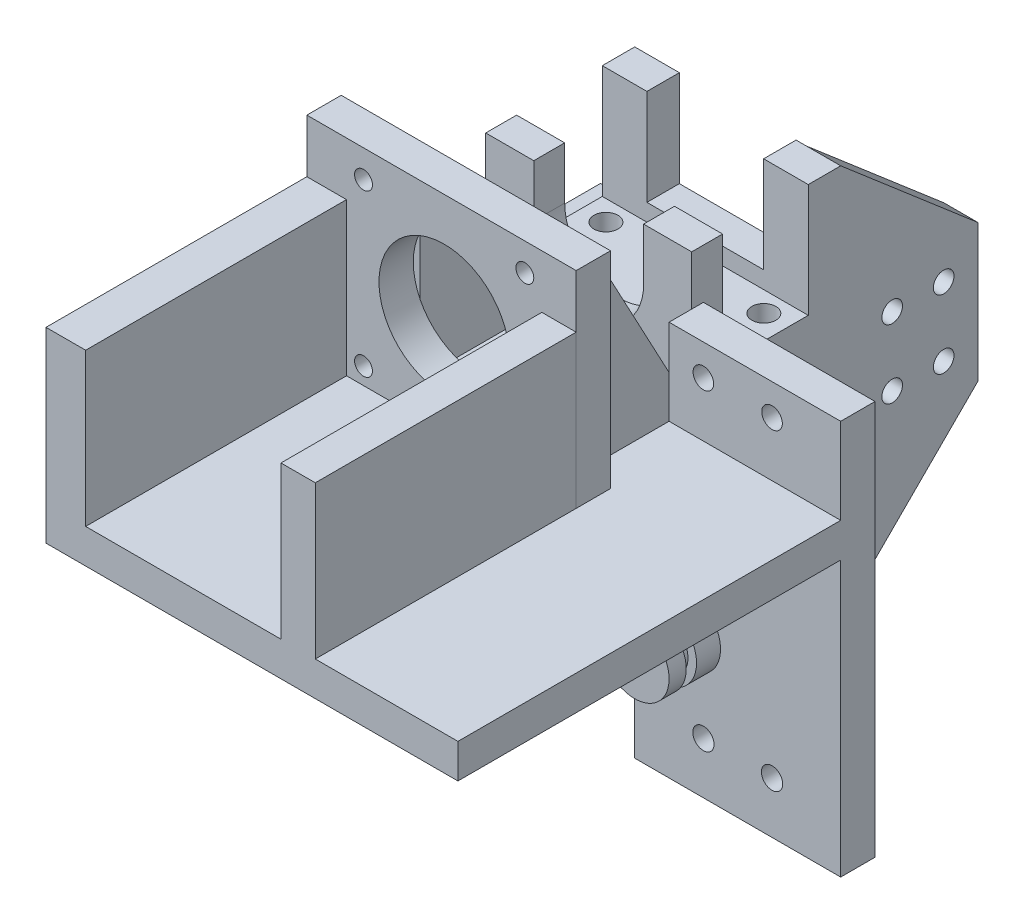
SolidWorks part; units mm, degrees
ref_plane "Front Plane" through (0, 0, 0) normal (0, 0, 1) x (1, 0, 0)
ref_plane "Top Plane" through (0, 0, 0) normal (0, 1, 0) x (1, 0, 0)
ref_plane "Right Plane" through (0, 0, 0) normal (1, 0, 0) x (0, 0, -1)
sketch "Sketch1" plane through (0, 0, 0) normal (0, 1, 0) x (1, 0, 0)
  line L0 (0, 0) -> (0, 161.51)
  line L1 (0, 161.51) -> (60, 161.51)
  line L2 (60, 161.51) -> (60, 121.51)
  line L3 (60, 121.51) -> (110, 121.51)
  line L4 (110, 121.51) -> (110, 0)
  line L5 (110, 0) -> (0, 0)
  dimension "D1" = 161.51
  dimension "D2" = 60
  dimension "D3" = 50
  dimension "D4" = 121.51
extrude "Boss-Extrude1" add sketch "Sketch1" along normal blind 10
sketch "Sketch2" plane through (0, 10, 0) normal (0, 1, 0) x (1, 0, 0)
  line L0 (0, 161.51) -> (0, 0) construction
  line L1 (0, 152.1) -> (60, 152.1)
  line L2 (0, 152.1) -> (0, 127.1)
  line L3 (0, 127.1) -> (60, 127.1)
  line L4 (60, 152.1) -> (60, 127.1)
  line L5 (60, 121.51) -> (60, 161.51) construction
  line L6 (60, 161.51) -> (0, 161.51) construction
  dimension "D1" = 9.41
  dimension "D2" = 25
extrude "Boss-Extrude2" add sketch "Sketch2" along normal blind 6.45
sketch "Sketch3" plane through (0, 10, 0) normal (0, 1, 0) x (1, 0, 0)
  line L0 (60, 152.1) -> (60, 161.51) construction
  line L1 (0, 161.51) -> (60, 161.51)
  line L2 (0, 161.51) -> (0, 152.06)
  line L3 (0, 152.06) -> (60, 152.06)
  line L4 (60, 161.51) -> (60, 152.06)
  dimension "D1" = 9.45
extrude "Boss-Extrude3" add sketch "Sketch3" along normal blind 39.45
sketch "Sketch4" plane through (0, 0, -161.51) normal (0, 0, -1) x (-1, 0, 0)
  line L0 (-60, 49.45) -> (0, 49.45) construction
  line L1 (-47, 49.45) -> (-13, 49.45)
  line L2 (-47, 49.45) -> (-47, 21.45)
  line L3 (-47, 21.45) -> (-13, 21.45)
  line L4 (-13, 49.45) -> (-13, 21.45)
  line L5 (-60, 49.45) -> (-60, 0) construction
  line L6 (0, 49.45) -> (0, 0) construction
  dimension "D1" = 13
  dimension "D2" = 13
  dimension "D3" = 28
extrude "Cut-Extrude1" cut sketch "Sketch4" against normal blind 9.45
sketch "Sketch5" plane through (0, 10, 0) normal (0, 1, 0) x (1, 0, 0)
  line L0 (60, 127.1) -> (60, 152.06) construction
  line L1 (0, 127.1) -> (60, 127.1)
  line L2 (0, 127.1) -> (0, 118.1)
  line L3 (0, 118.1) -> (60, 118.1)
  line L4 (60, 127.1) -> (60, 118.1)
  dimension "D1" = 9
extrude "Boss-Extrude4" add sketch "Sketch5" along normal blind 39.45
sketch "Sketch6" plane through (0, 0, -118.1) normal (0, 0, 1) x (1, 0, 0)
  line L0 (30, 49.45) -> (30, 10) construction
  line L1 (0, 49.45) -> (60, 49.45) construction
  line L2 (0, 10) -> (60, 10) construction
  line L3 (14, 34.24) -> (14, 49.45)
  line L4 (14, 49.45) -> (46, 49.45)
  line L5 (46, 49.45) -> (46, 34.24)
  arc A0 (14, 34.24) -> (46, 34.24) centre (30, 34.24) ccw
  dimension "D1" = 16
  dimension "D2" = 15.21
extrude "Cut-Extrude2" cut sketch "Sketch6" against normal up to next
sketch "Sketch7" plane through (0, 0, 0) normal (0, -1, 0) x (1, 0, 0)
  line L0 (110, -111.51) -> (50, -111.51)
  line L1 (110, 0) -> (110, -121.51) construction
  line L2 (50, -111.51) -> (50, -161.51)
  line L3 (60, -161.51) -> (0, -161.51) construction
  line L4 (50, -161.51) -> (60, -161.51)
  line L5 (60, -161.51) -> (60, -121.51)
  line L6 (60, -121.51) -> (110, -121.51)
  line L7 (110, -121.51) -> (110, -111.51)
  dimension "D1" = 10
  dimension "D2" = 10
extrude "Boss-Extrude5" add sketch "Sketch7" along normal blind 80
sketch "Sketch8" plane through (0, 0, 0) normal (-1, 0, 0) x (0, 0, 1)
  line L0 (-161.51, 0) -> (0, 0) construction
  line L1 (-75.9971, 0) -> (0, 0)
  line L2 (-75.9971, 0) -> (-75.9971, 54.4584)
  line L3 (-75.9971, 54.4584) -> (0, 54.4584)
  line L4 (0, 0) -> (0, 54.4584)
  line L5 (0, 10) -> (0, 0) construction
  dimension "D1" = 75.9971
extrude "Boss-Extrude6" add sketch "Sketch8" along normal blind 10
sketch "Sketch9" plane through (0, 10, 0) normal (0, 1, 0) x (1, 0, 0)
  line L0 (0, 0) -> (110, 0) construction
  line L1 (58.45, 75.9971) -> (68.45, 75.9971)
  line L2 (58.45, 75.9971) -> (58.45, 0)
  line L3 (58.45, 0) -> (68.45, 0)
  line L4 (68.45, 75.9971) -> (68.45, 0)
  line L5 (0, 0) -> (0, 75.9971) construction
  line L6 (-10, 75.9971) -> (0, 75.9971) construction
  dimension "D1" = 58.45
  dimension "D2" = 10
extrude "Boss-Extrude7" add sketch "Sketch9" along normal blind 44.46
sketch "Sketch17" plane through (0, 10, 0) normal (0, 1, 0) x (1, 0, 0)
  line L0 (0, 0) -> (58.45, 0) construction
  line L1 (68.45, 86) -> (-10, 86)
  line L2 (68.45, 86) -> (68.45, 76)
  line L3 (68.45, 76) -> (-10, 76)
  line L4 (-10, 86) -> (-10, 76)
  line L5 (-10, 0) -> (-10, 75.9971) construction
  dimension "D1" = 78.45
  dimension "D2" = 10
  dimension "D3" = 76
  dimension "D4" = 78.45
extrude "Boss-Extrude27" add sketch "Sketch17" along normal blind 60
sketch "Sketch19" plane through (0, 0, -86) normal (0, 0, -1) x (-1, 0, 0)
  line L0 (0, 10) -> (10, 10) construction
  line L1 (0, 70) -> (-2.5, 70)
  line L2 (0, 70) -> (0, 10)
  line L3 (0, 10) -> (-2.5, 10)
  line L4 (-2.5, 70) -> (-2.5, 10)
  line L5 (10, 70) -> (10, 10) construction
  line L6 (-68.45, 70) -> (10, 70) construction
  line L7 (-13, 70) -> (-10.5, 70)
  line L8 (-13, 70) -> (-13, 10)
  line L9 (-13, 10) -> (-10.5, 10)
  line L10 (-10.5, 70) -> (-10.5, 10)
  line L12 (-47, 70) -> (-49.5, 70)
  line L13 (-47, 70) -> (-47, 10)
  line L14 (-47, 10) -> (-49.5, 10)
  line L15 (-49.5, 70) -> (-49.5, 10)
  line L16 (-57.5, 70) -> (-60, 70)
  line L17 (-57.5, 70) -> (-57.5, 10)
  line L18 (-57.5, 10) -> (-60, 10)
  line L19 (-60, 70) -> (-60, 10)
  dimension "D1" = 10
  dimension "D2" = 2.5
  dimension "D3" = 60
  dimension "D4" = 8
  dimension "D5" = 2.5
  dimension "D6" = 60
  dimension "D7" = 2.5
  dimension "D8" = 8
  dimension "D9" = 2.5
  dimension "D10" = 60
  dimension "D11" = 60
  dimension "D12" = 34
extrude "Boss-Extrude31" add sketch "Sketch19" along normal blind 32
sketch "Sketch20" plane through (0, 0, 0) normal (1, 0, 0) x (0, 0, -1)
  line L1 (0, 54.4584) -> (75.9971, 54.4584)
  line L2 (0, 54.4584) -> (0, 10)
  line L3 (0, 10) -> (75.9971, 10)
  line L4 (75.9971, 54.4584) -> (75.9971, 10)
extrude "Boss-Extrude32" add sketch "Sketch20" along normal blind 1.55
sketch "Sketch21" plane through (0, 0, -76) normal (0, 0, 1) x (1, 0, 0)
  line L0 (-10, 70) -> (-10, 10) construction
  line L1 (-10, 70) -> (68.45, 70) construction
  line L2 (53.5, 61.95) -> (6.5, 14.95) construction
  line L3 (53.5, 14.95) -> (6.5, 61.95) construction
  circle A0 centre (6.5, 61.95) radius 2.6
  circle A1 centre (53.5, 61.95) radius 2.6
  circle A2 centre (53.5, 14.95) radius 2.6
  circle A3 centre (6.5, 14.95) radius 2.6
  circle A4 centre (30, 38.45) radius 19
  dimension "D5" = 5.2
  dimension "D6" = 38
  dimension "D1" = 16.5
  dimension "D2" = 8.05
  dimension "D3" = 47
  dimension "D4" = 47
extrude "Cut-Extrude3" cut sketch "Sketch21" against normal blind 10
sketch "Sketch22" plane through (0, 0, 0) normal (0, -1, 0) x (1, 0, 0)
  line L0 (50, -161.51) -> (0, -161.51) construction
  line L1 (0, -161.51) -> (0, -75.9971) construction
  circle A0 centre (7.02, -146.1) radius 3.5
  circle A1 centre (7.02, -133) radius 3.5
  circle A2 centre (53.02, -146.1) radius 3.5
  circle A3 centre (53.02, -133) radius 3.5
  dimension "D4" = 7
  dimension "D1" = 13.1
  dimension "D2" = 15.41
  dimension "D3" = 7.02
  dimension "D5" = 46
extrude "Cut-Extrude4" cut sketch "Sketch22" against normal up to next
sketch "Sketch23" plane through (50, 0, 0) normal (-1, 0, 0) x (0, 0, 1)
  line L0 (-147.8691, 0) -> (-161.51, 0) construction
  line L1 (-153.1, 0) -> (-126.1, 0)
  line L2 (-153.1, 0) -> (-153.1, -6)
  line L3 (-153.1, -6) -> (-126.1, -6)
  line L4 (-126.1, 0) -> (-126.1, -6)
  line L10 (-161.51, -80) -> (-161.51, 0) construction
  dimension "D1" = 27
  dimension "D2" = 8.41
  dimension "D3" = 6
extrude "Cut-Extrude5" cut sketch "Sketch23" against normal up to next
sketch "Sketch24" plane through (50, 0, 0) normal (-1, 0, 0) x (0, 0, 1)
  line L0 (-161.51, -80) -> (-161.51, 0) construction
  line L1 (-111.51, -80) -> (-111.51, 0) construction
  line L2 (-111.51, -80) -> (-161.51, -80) construction
  circle A0 centre (-151.51, -15) radius 3.1
  circle A1 centre (-151.51, -65) radius 3.1
  circle A2 centre (-131.51, -15) radius 3.1
  circle A3 centre (-131.51, -65) radius 3.1
  dimension "D5" = 6.2
  dimension "D1" = 10
  dimension "D2" = 20
  dimension "D3" = 15
  dimension "D4" = 50
extrude "Cut-Extrude6" cut sketch "Sketch24" against normal up to next
sketch "Sketch25" plane through (0, 0, -111.51) normal (0, 0, 1) x (1, 0, 0)
  line L0 (50, -80) -> (50, 0) construction
  line L1 (110, -80) -> (50, -80) construction
  circle A0 centre (70, -15) radius 3.1
  circle A1 centre (90, -15) radius 3.1
  circle A2 centre (70, -65) radius 3.1
  circle A3 centre (90, -65) radius 3.1
  dimension "D5" = 6.2
  dimension "D1" = 20
  dimension "D2" = 20
  dimension "D3" = 15
  dimension "D4" = 50
extrude "Cut-Extrude7" cut sketch "Sketch25" against normal up to next
sketch "Sketch26" plane through (0, 0, 0) normal (-1, 0, 0) x (0, 0, 1)
  line L2 (-118.1, 10) -> (-86, 70)
  line L3 (-86, 70) -> (-118, 70)
  line L4 (-118, 70) -> (-118.1, 10)
extrude "Cut-Extrude10" cut sketch "Sketch26" against normal blind 70
sketch "Sketch27" plane through (0, 10, 0) normal (0, 1, 0) x (1, 0, 0)
  line L0 (60, 118) -> (60, 86) construction
  line L1 (110, 121.51) -> (60, 121.51)
  line L2 (110, 121.51) -> (110, 111.51)
  line L3 (110, 111.51) -> (60, 111.51)
  line L4 (60, 121.51) -> (60, 111.51)
  dimension "D1" = 10
extrude "Boss-Extrude33" add sketch "Sketch27" along normal blind 25
sketch "Sketch28" plane through (0, 0, -111.51) normal (0, 0, 1) x (1, 0, 0)
  line L0 (110, 35) -> (110, 10) construction
  line L1 (60, 35) -> (110, 35) construction
  circle A0 centre (90, 25.935) radius 3
  circle A1 centre (70, 25.935) radius 3
  dimension "D1" = 6
  dimension "D2" = 20
  dimension "D3" = 20
  dimension "D4" = 9.065
extrude "Cut-Extrude11" cut sketch "Sketch28" against normal up to next
sketch "Sketch29" plane through (0, 0, -161.51) normal (0, 0, -1) x (-1, 0, 0)
  line L0 (-60, 49.45) -> (-60, -80) construction
  line L1 (-60, 15.15) -> (-50, 15.15)
  line L2 (-60, 15.15) -> (-60, -24.85)
  line L3 (-60, -24.85) -> (-50, -24.85)
  line L4 (-50, 15.15) -> (-50, -24.85)
  line L5 (-50, -80) -> (-50, 0) construction
  line L6 (-60, 49.45) -> (-47, 49.45) construction
  dimension "D1" = 40
  dimension "D2" = 34.3
extrude "Boss-Extrude34" add sketch "Sketch29" along normal blind 40
sketch "Sketch30" plane through (50, 0, 0) normal (-1, 0, 0) x (0, 0, 1)
  line L0 (-201.51, 15.15) -> (-161.51, 15.15) construction
  line L1 (-201.51, -24.85) -> (-161.51, -24.85) construction
  line L2 (-201.51, -24.85) -> (-201.51, 15.15) construction
  circle A0 centre (-191.51, 5.15) radius 3
  circle A1 centre (-176.51, 5.15) radius 3
  circle A2 centre (-191.51, -14.85) radius 3
  circle A3 centre (-176.51, -14.85) radius 3
  dimension "D1" = 6
  dimension "D2" = 10
  dimension "D3" = 10
  dimension "D4" = 10
  dimension "D5" = 15
extrude "Cut-Extrude12" cut sketch "Sketch30" against normal up to next
sketch "Sketch31" plane through (50, 0, 0) normal (-1, 0, 0) x (0, 0, 1)
  line L0 (-161.51, 15.15) -> (-161.51, 49.45)
  line L1 (-161.51, 49.45) -> (-201.51, 15.15)
  line L2 (-201.51, 15.15) -> (-161.51, 15.15)
  line L3 (-161.51, -24.85) -> (-201.51, -24.85)
  line L4 (-201.51, -24.85) -> (-161.51, -64.85)
  line L5 (-161.51, -80) -> (-161.51, -24.85) construction
  line L6 (-161.51, -64.85) -> (-161.51, -24.85)
  dimension "D1" = 45
extrude "Boss-Extrude35" add sketch "Sketch31" against normal blind 10
sketch "Sketch32" plane through (50, 0, 0) normal (-1, 0, 0) x (0, 0, 1)
  line L0 (-111.51, -80) -> (-111.51, 0) construction
  line L1 (-111.51, -80) -> (-161.51, -80) construction
  circle A0 centre (-126.51, -40) radius 10
  dimension "D1" = 20
  dimension "D2" = 15
  dimension "D3" = 40
extrude "Boss-Extrude36" add sketch "Sketch32" along normal blind 15
sketch "Sketch33" plane through (35, 0, 0) normal (-1, 0, 0) x (0, 0, 1)
  line L0 (-126.51, -30) -> (-126.51, -50) construction
  circle A0 centre (-126.51, -40) radius 10 construction
  circle A1 centre (-126.51, -40) radius 10 construction
  circle A2 centre (-126.51, -40) radius 7.5
  circle A3 centre (-126.51, -40) radius 10
  dimension "D1" = 20
  dimension "D2" = 15
extrude "Cut-Extrude14" cut sketch "Sketch33" against normal blind 3 from offset 5 offset against normal yes
sketch "Sketch34" plane through (0, 0, 0) normal (-1, 0, 0) x (0, 0, 1)
  line L1 (-76, 10) -> (-161.51, 10)
  line L2 (-76, 10) -> (-76, 0)
  line L3 (-76, 0) -> (-161.51, 0)
  line L4 (-161.51, 10) -> (-161.51, 0)
extrude "Boss-Extrude37" add sketch "Sketch34" along normal blind 10
sketch "Sketch35" plane through (0, 0, -111.51) normal (0, 0, 1) x (1, 0, 0)
  line L0 (110, -80) -> (50, -80) construction
  line L1 (50, -80) -> (50, 0) construction
  circle A0 centre (65, -40) radius 10
  dimension "D1" = 20
  dimension "D2" = 40
  dimension "D3" = 15
extrude "Boss-Extrude38" add sketch "Sketch35" along normal blind 15
sketch "Sketch37" plane through (0, 0, -96.51) normal (0, 0, 1) x (1, 0, 0)
  line L0 (65, -30) -> (65, -50) construction
  circle A0 centre (65, -40) radius 10 construction
  circle A1 centre (65, -40) radius 10 construction
  circle A2 centre (65, -40) radius 10
  circle A3 centre (65, -40) radius 7.5
  dimension "D1" = 20
  dimension "D2" = 15
extrude "Cut-Extrude15" cut sketch "Sketch37" against normal blind 3 from offset 5
